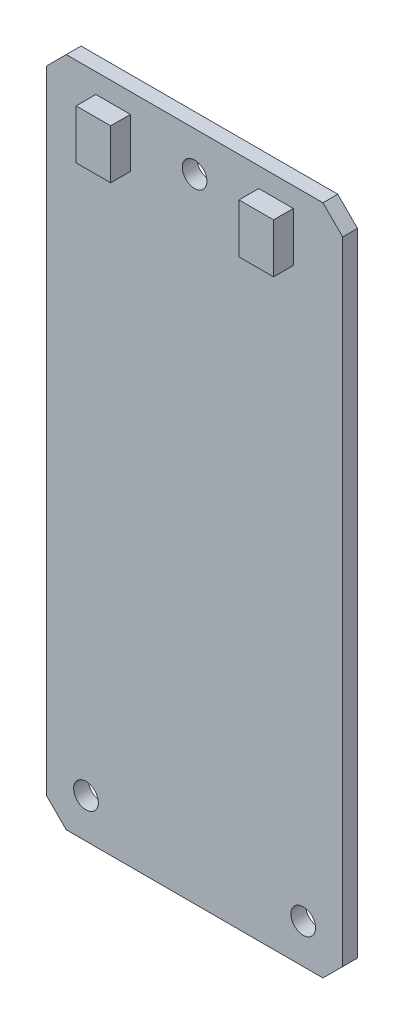
SolidWorks part; units mm, degrees
ref_plane "Спереди" through (0, 0, 0) normal (0, 0, 1) x (1, 0, 0)
ref_plane "Сверху" through (0, 0, 0) normal (0, 1, 0) x (1, 0, 0)
ref_plane "Справа" through (0, 0, 0) normal (1, 0, 0) x (0, 0, -1)
sketch "Эскиз1" plane through (0, 0, 0) normal (0, 0, 1) x (1, 0, 0)
  line L1 (0, 68) -> (30, 68)
  line L2 (0, 68) -> (0, 0)
  line L3 (0, 0) -> (30, 0)
  line L4 (30, 68) -> (30, 0)
  circle A2 centre (15, 64) radius 1.25
  circle A3 centre (4, 4) radius 1.25
  circle A4 centre (26, 4) radius 1.25
  point P5 (15, 64)
  point P7 (15, 68)
  point P8 (4, 4)
  point P9 (26, 4)
  dimension "D1" = 30
  dimension "D7" = 2.5
  dimension "D2" = 68
  dimension "D3" = 4
  dimension "D4" = 4
  dimension "D5" = 4
  dimension "D6" = 4
extrude "Бобышка-Вытянуть6" add sketch "Эскиз1" along normal blind 1.5
chamfer "Фаска2" distance 2 angle 45 4 edges at (30, 0, 0.75) (0, 0, 0.75) (30, 68, 0.75) (0, 68, 0.75)
sketch "Эскиз3" [suppressed] plane through (0, 0, 1.5) normal (0, 0, 1) x (1, 0, 0)
  line L1 (-15, -15) -> (15, -15)
  line L2 (-15, -15) -> (-15, 15)
  line L3 (-15, 15) -> (15, 15)
  line L4 (15, -15) -> (15, 15)
  line L5 (-15, -15) -> (15, 15) construction
  line L6 (-15, 15) -> (15, -15) construction
  point P0 (0, 0)
  point P3 (0, 0)
  dimension "D1" = 30
extrude "Бобышка-Вытянуть3" [suppressed] add sketch "Эскиз3" along normal blind 3
sketch "Эскиз4" [suppressed] plane through (0, 0, 1.5) normal (0, 0, 1) x (1, 0, 0)
  line L0 (15, -15) -> (15, 15) construction
  line L1 (-15, -35) -> (15, -35)
  line L2 (-15, -35) -> (-15, 35)
  line L3 (-15, 35) -> (15, 35)
  line L4 (15, -35) -> (15, 35)
  line L5 (-15, 15) -> (-15, -15) construction
  dimension "D1" = 35
  dimension "D2" = 35
extrude "Бобышка-Вытянуть4" [suppressed] add sketch "Эскиз4" against normal up to surface (1.5 mm away)
sketch "Эскиз5" [suppressed] plane through (0, 0, 1.5) normal (0, 0, 1) x (1, 0, 0)
  line L0 (-15, 35) -> (15, 35) construction
  line L1 (-15, -35) -> (15, -35) construction
  line L3 (-15, 20) -> (-15, 35) construction
  line L4 (15, -35) -> (15, -20) construction
  circle A0 centre (-11, 31) radius 1.25
  circle A1 centre (11, 31) radius 1.25
  circle A2 centre (-11, -31) radius 1.25
  circle A3 centre (11, -31) radius 1.25
  point P0 (-11, 31)
  point P1 (11, 31)
  point P2 (-11, -31)
  point P3 (11, -31)
  dimension "D5" = 2.5
  dimension "D1" = 4
  dimension "D2" = 4
  dimension "D3" = 4
  dimension "D4" = 4
extrude "Вырез-Вытянуть1" [suppressed] cut sketch "Эскиз5" against normal through all
sketch "Эскиз7" [suppressed] plane through (0, 0, 1.5) normal (0, 0, 1) x (1, 0, 0)
  line L0 (15, -35) -> (15, -20) construction
  line L1 (-15, 20) -> (-25, 20)
  line L2 (-15, 20) -> (-15, -20)
  line L3 (-15, -20) -> (-25, -20)
  line L4 (-25, 20) -> (-25, -20)
  line L5 (15, 20) -> (25, 20)
  line L6 (15, 20) -> (15, -20)
  line L7 (15, -20) -> (25, -20)
  line L8 (25, 20) -> (25, -20)
  line L9 (-15, -35) -> (-15, -20) construction
  arc A0 (-15, 20) -> (-15, -20) centre (0, 0) ccw construction
  arc A1 (15, -20) -> (15, 20) centre (0, 0) ccw construction
extrude "Вырез-Вытянуть2" [suppressed] cut sketch "Эскиз7" against normal through all
chamfer "Фаска1" [suppressed] distance 2 angle 45
sketch "Эскиз9" plane through (0, 0, 1.5) normal (0, 0, 1) x (1, 0, 0)
  line L1 (5, 66) -> (8.5, 66)
  line L2 (5, 66) -> (5, 61)
  line L3 (5, 61) -> (8.5, 61)
  line L4 (8.5, 66) -> (8.5, 61)
  line L6 (25, 66) -> (21.5, 66)
  line L7 (25, 66) -> (25, 61)
  line L8 (25, 61) -> (21.5, 61)
  line L9 (21.5, 66) -> (21.5, 61)
  line L10 (0, 66) -> (0, 2) construction
  line L11 (30, 2) -> (30, 66) construction
  line L12 (28, 68) -> (2, 68) construction
  dimension "D1" = 5
  dimension "D2" = 3.5
  dimension "D3" = 5
  dimension "D4" = 5
  dimension "D5" = 2
extrude "Бобышка-Вытянуть7" add sketch "Эскиз9" along normal blind 2
